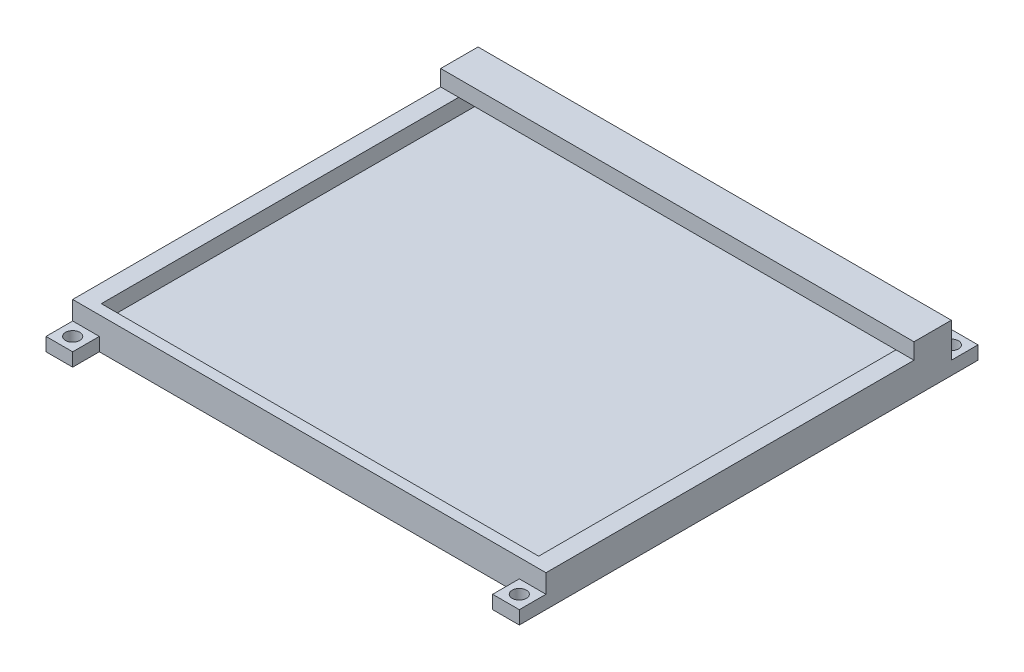
SolidWorks part; units mm, degrees
ref_plane "Front Plane" through (0, 0, 0) normal (0, 0, 1) x (1, 0, 0)
ref_plane "Top Plane" through (0, 0, 0) normal (0, 1, 0) x (1, 0, 0)
ref_plane "Right Plane" through (0, 0, 0) normal (1, 0, 0) x (0, 0, -1)
sketch "Sketch1" plane through (0, 0, 0) normal (0, 1, 0) x (1, 0, 0)
  line L1 (0, 0) -> (112.7, 0)
  line L2 (0, 0) -> (0, 96.52)
  line L3 (0, 96.52) -> (112.7, 96.52)
  line L4 (112.7, 0) -> (112.7, 96.52)
  dimension "D1" = 112.7
  dimension "D2" = 96.52
extrude "Boss-Extrude1" add sketch "Sketch1" along normal blind 7.62
sketch "Sketch2" plane through (0, 7.62, 0) normal (0, 1, 0) x (1, 0, 0)
  line L0 (0, 0) -> (112.7, 0) construction
  line L1 (4.28, 2.54) -> (108.42, 2.54)
  line L2 (4.28, 2.54) -> (4.28, 93.98)
  line L3 (4.28, 93.98) -> (108.42, 93.98)
  line L4 (108.42, 2.54) -> (108.42, 93.98)
  line L6 (0, 96.52) -> (0, 0) construction
  point P6 (56.35, 2.54)
  point P7 (56.35, 0)
  point P8 (4.28, 48.26)
  point P11 (0, 48.26)
  dimension "D1" = 104.14
  dimension "D2" = 91.44
  dimension "D3" = 0
  dimension "D4" = 0
extrude "Cut-Extrude1" cut sketch "Sketch2" against normal blind 3.81
sketch "Sketch3" plane through (0, 0, 0) normal (0, -1, 0) x (1, 0, 0)
  line L1 (112.7, 0) -> (106.35, 0)
  line L2 (112.7, 0) -> (112.7, 6.35)
  line L3 (112.7, 6.35) -> (106.35, 6.35)
  line L4 (106.35, 0) -> (106.35, 6.35)
  line L5 (0, 0) -> (6.35, 0)
  line L6 (0, 0) -> (0, 6.35)
  line L7 (0, 6.35) -> (6.35, 6.35)
  line L8 (6.35, 0) -> (6.35, 6.35)
  line L9 (0, -96.52) -> (6.35, -96.52)
  line L10 (0, -96.52) -> (0, -102.87)
  line L11 (0, -102.87) -> (6.35, -102.87)
  line L12 (6.35, -96.52) -> (6.35, -102.87)
  line L13 (112.7, -96.52) -> (106.35, -96.52)
  line L14 (112.7, -96.52) -> (112.7, -102.87)
  line L15 (112.7, -102.87) -> (106.35, -102.87)
  line L16 (106.35, -96.52) -> (106.35, -102.87)
  circle A0 centre (3.175, 3.175) radius 1.7
  circle A1 centre (109.525, 3.175) radius 1.7
  circle A2 centre (3.175, -99.695) radius 1.7
  circle A3 centre (109.525, -99.695) radius 1.7
  point P28 (3.175, -99.695)
  point P29 (109.525, -99.695)
  dimension "D9" = 3.4
  dimension "D10" = 3.4
  dimension "D11" = 3.4
  dimension "D12" = 3.4
  dimension "D1" = 6.35
  dimension "D2" = 6.35
  dimension "D3" = 6.35
  dimension "D4" = 6.35
  dimension "D5" = 6.35
  dimension "D6" = 6.35
  dimension "D7" = 6.35
  dimension "D8" = 6.35
extrude "Boss-Extrude2" add sketch "Sketch3" against normal blind 3.175
sketch "Sketch4" plane through (0, 7.62, 0) normal (0, 1, 0) x (1, 0, 0)
  line L0 (112.7, 0) -> (112.7, 96.52) construction
  line L1 (0, 96.52) -> (112.7, 96.52)
  line L2 (0, 96.52) -> (0, 87.63)
  line L3 (0, 87.63) -> (112.7, 87.63)
  line L4 (112.7, 96.52) -> (112.7, 87.63)
  line L6 (108.42, 93.98) -> (4.28, 93.98) construction
  dimension "D1" = 8.89
  dimension "D2" = 2.54
extrude "Boss-Extrude3" add sketch "Sketch4" along normal blind 3.81
